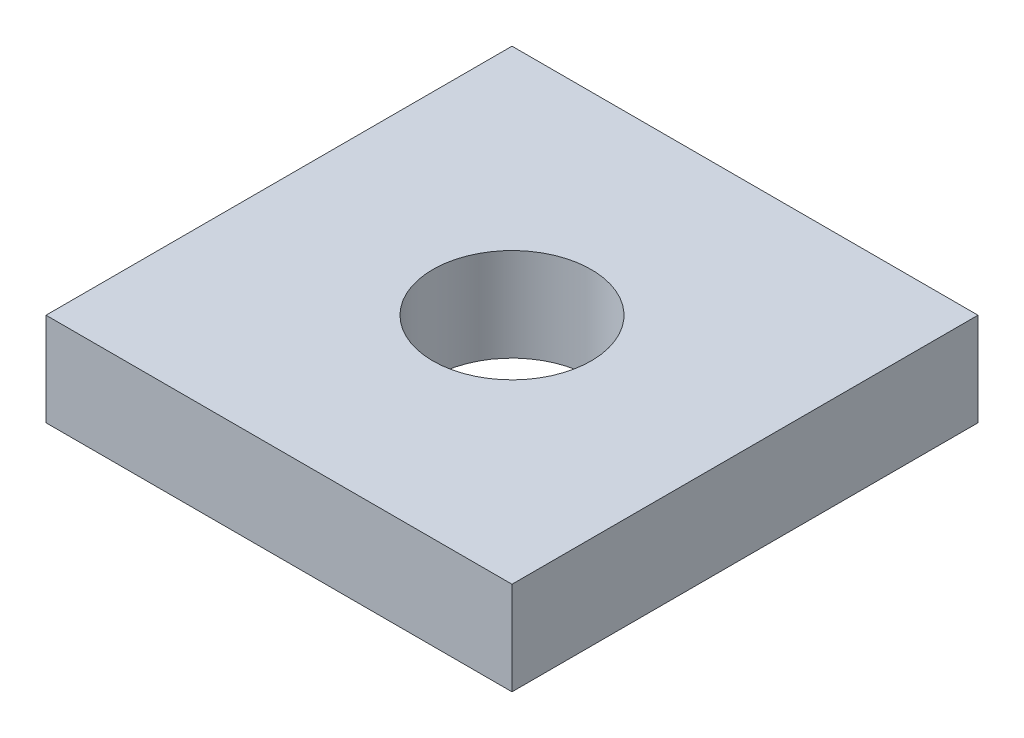
SolidWorks part; units mm, degrees
material "AISI 1020"
ref_plane "Front Plane" through (0, 0, 0) normal (0, 0, 1) x (1, 0, 0)
ref_plane "Top Plane" through (0, 0, 0) normal (0, 1, 0) x (1, 0, 0)
ref_plane "Right Plane" through (0, 0, 0) normal (1, 0, 0) x (0, 0, -1)
sketch "Sketch1" plane through (0, 0, 0) normal (0, 0, 1) x (1, 0, 0)
  line L1 (-10, -2) -> (10, -2)
  line L2 (-10, -2) -> (-10, 2)
  line L3 (-10, 2) -> (10, 2)
  line L4 (10, -2) -> (10, 2)
  line L5 (-10, -2) -> (10, 2) construction
  line L6 (-10, 2) -> (10, -2) construction
  point P0 (0, 0)
  dimension "D1" = 4
  dimension "D2" = 20
extrude "Boss-Extrude1" add sketch "Sketch1" along normal mid plane 20
hole_wizard "M8x1.25 Tapped Hole1" positions "Sketch3" profile "Sketch5" tap size "M8x1.25" standard "ANSI Metric" end condition up to next
sketch "Sketch3" plane through (0, 2, 0) normal (0, 1, 0) x (1, 0, 0)
  point P0 (0, 0)
cosmetic thread "Hole Thread1" parameters "D2"=8
sketch "Sketch5" plane through (0, 2, 0) normal (1, 0, 0) x (0, 0, 1)
  line L0 (0, 0) -> (0, 4)
  line L1 (0, 4) -> (3.4, 4)
  line L2 (3.4, 4) -> (3.4, 0)
  line L5 (3.4, 0) -> (0, 0)
  line L11 (0, -6.35) -> (0, 107.95) construction
  dimension "Thru Tap Drill Dia." = 6.8
  dimension "Thru Tap Drill Depth" = 4
